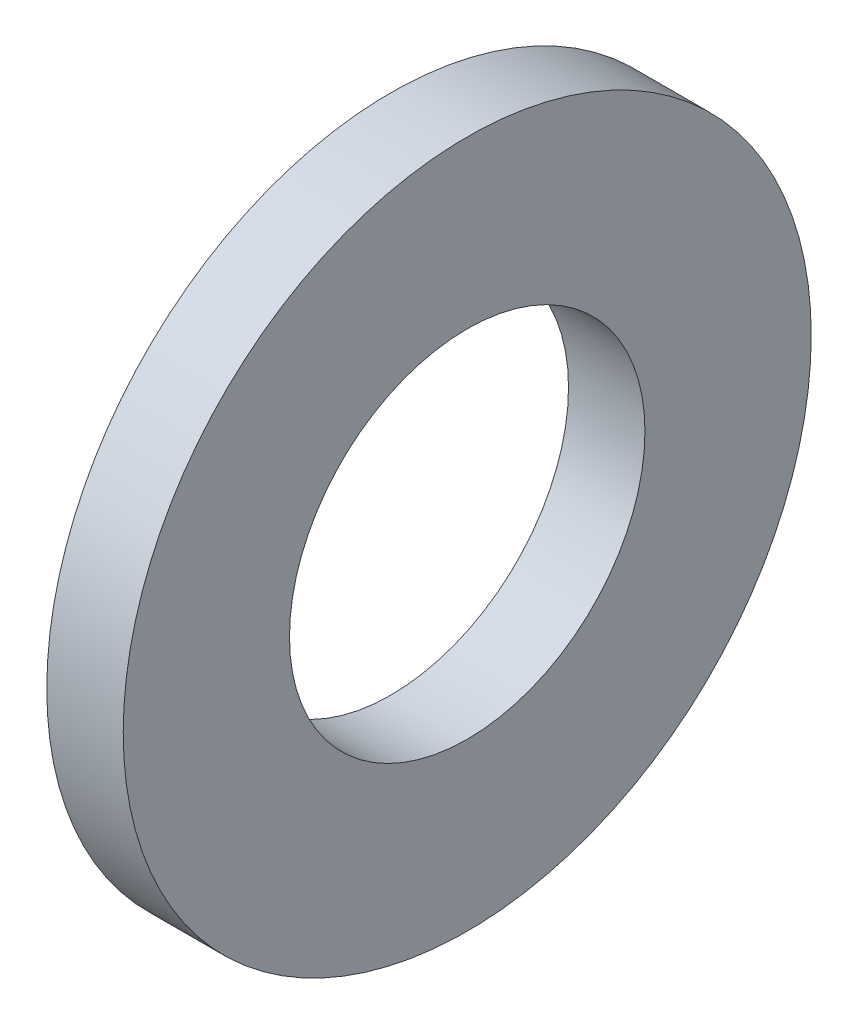
SolidWorks part; units mm, degrees
ref_plane "Plane1" through (0, 0, 0) normal (0, 0, 1) x (1, 0, 0)
ref_plane "Plane2" through (0, 0, 0) normal (0, 1, 0) x (1, 0, 0)
ref_plane "Plane3" through (0, 0, 0) normal (1, 0, 0) x (0, 0, -1)
sketch "Sketch1" plane through (0, 0, 0) normal (1, 0, 0) x (0, 0, -1)
  circle A0 centre (0, 0) radius 4.65
  circle A1 centre (0, 0) radius 9
  dimension "Insid_dia" = 9.3
  dimension "OutsideDia" = 18
extrude "Base-Extrude" add sketch "Sketch1" along normal blind 2
